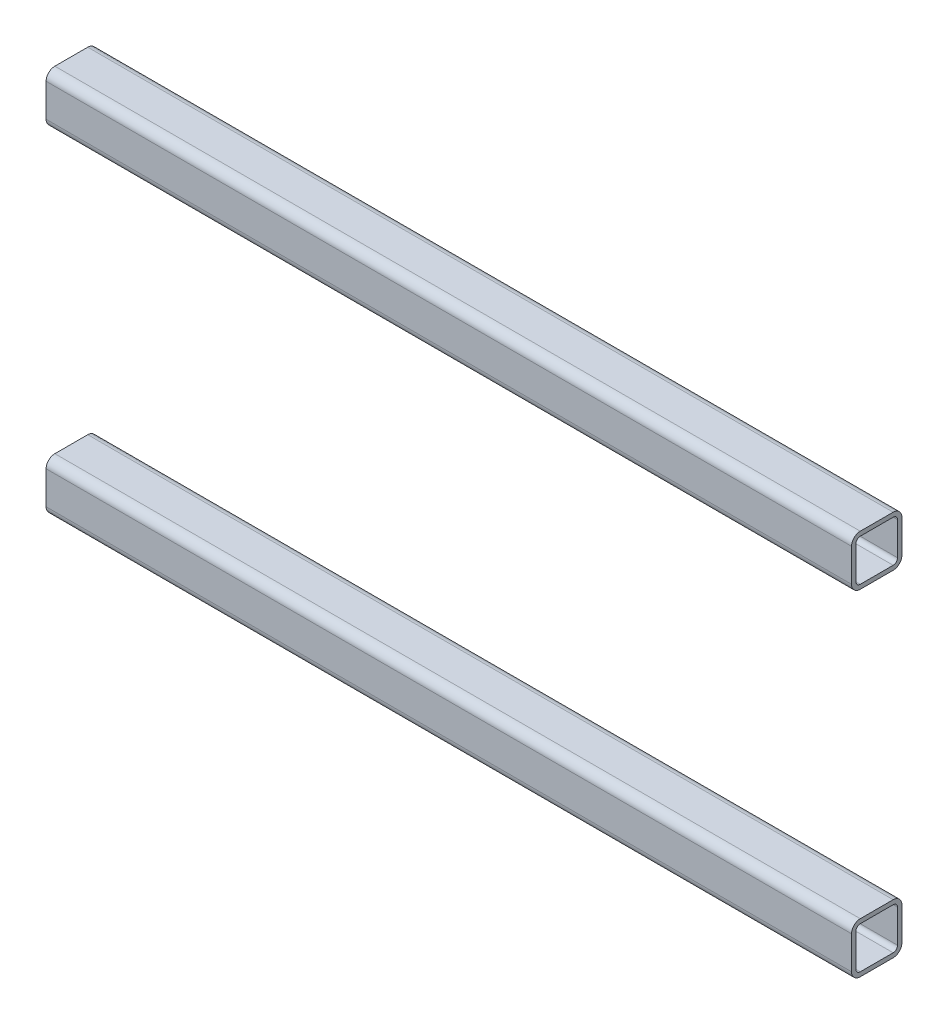
SolidWorks part; units mm, degrees
ref_plane "前视基准面" through (0, 0, 0) normal (0, 0, 1) x (1, 0, 0)
ref_plane "上视基准面" through (0, 0, 0) normal (0, 1, 0) x (1, 0, 0)
ref_plane "右视基准面" through (0, 0, 0) normal (1, 0, 0) x (0, 0, -1)
sketch3d "3D草图1"
  line L0 (0, 0, 0) -> (480, 0, 0)
  line L1 (0, 0, 0) -> (0, 200, 0) construction
  line L2 (0, 200, 0) -> (480, 200, 0)
  dimension "D1" = 200
  dimension "D2" = 480
other "Square tube - configured 30 X 30 X 2.6(1)"
ref_plane "基准面1" through (0, 200, 0) normal (1, 0, 0) x (0, 0, -1)
sketch "Sketch1" plane through (0, 200, 0) normal (1, 0, 0) x (0, 0, -1)
  line L0 (-9.8, -12.4) -> (9.8, -12.4)
  line L1 (-12.4, -9.8) -> (-12.4, 9.8)
  line L2 (9.8, 12.4) -> (-9.8, 12.4)
  line L3 (12.4, 9.8) -> (12.4, -9.8)
  line L4 (-9.8, -15) -> (9.8, -15)
  line L5 (-15, -9.8) -> (-15, 9.8)
  line L6 (9.8, 15) -> (-9.8, 15)
  line L7 (15, 9.8) -> (15, -9.8)
  arc A0 (15, 9.8) -> (9.8, 15) centre (9.8, 9.8) ccw
  arc A1 (9.8, -15) -> (15, -9.8) centre (9.8, -9.8) ccw
  arc A2 (-15, -9.8) -> (-9.8, -15) centre (-9.8, -9.8) ccw
  arc A3 (-9.8, 15) -> (-15, 9.8) centre (-9.8, 9.8) ccw
  arc A4 (-9.8, 12.4) -> (-12.4, 9.8) centre (-9.8, 9.8) ccw
  arc A5 (12.4, 9.8) -> (9.8, 12.4) centre (9.8, 9.8) ccw
  arc A6 (9.8, -12.4) -> (12.4, -9.8) centre (9.8, -9.8) ccw
  arc A7 (-12.4, -9.8) -> (-9.8, -12.4) centre (-9.8, -9.8) ccw
  point P0 (-15, 0)
  point P1 (15, 0)
  point P2 (0, 15)
  point P3 (0, -15)
  point P4 (0, 0)
  point P5 (-15, -15)
  point P6 (15, -15)
  point P7 (15, 15)
  point P8 (-15, 15)
  point P33 (0, 0)
  dimension "D1" = 5.2
  dimension "Thickness" = 2.6
  dimension "V_leg" = 30
